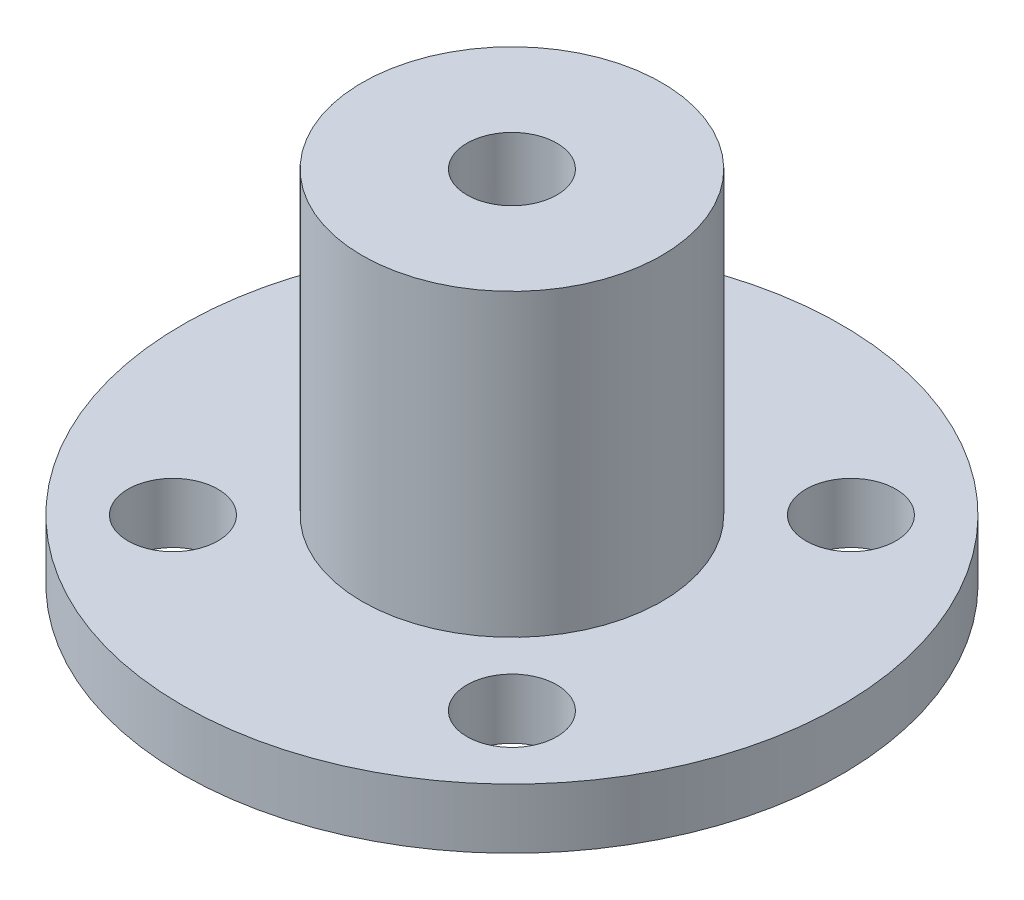
SolidWorks part; units mm, degrees
ref_plane "前视基准面" through (0, 0, 0) normal (0, 0, 1) x (1, 0, 0)
ref_plane "上视基准面" through (0, 0, 0) normal (0, 1, 0) x (1, 0, 0)
ref_plane "右视基准面" through (0, 0, 0) normal (1, 0, 0) x (0, 0, -1)
other "Configuration Table"
sketch "草图1" plane through (0, 0, 0) normal (0, 1, 0) x (1, 0, 0)
  line L1 (-5.6569, -5.6569) -> (5.6569, -5.6569) construction
  line L2 (-5.6569, -5.6569) -> (-5.6569, 5.6569) construction
  line L3 (-5.6569, 5.6569) -> (5.6569, 5.6569) construction
  line L4 (5.6569, -5.6569) -> (5.6569, 5.6569) construction
  line L5 (-5.6569, -5.6569) -> (5.6569, 5.6569) construction
  line L6 (-5.6569, 5.6569) -> (5.6569, -5.6569) construction
  circle A0 centre (0, 0) radius 11
  circle A1 centre (0, 0) radius 1.5
  circle A2 centre (0, 0) radius 8 construction
  circle A3 centre (5.6569, 5.6569) radius 1.5
  circle A4 centre (-5.6569, 5.6569) radius 1.5
  circle A5 centre (-5.6569, -5.6569) radius 1.5
  circle A6 centre (5.6569, -5.6569) radius 1.5
  dimension "D1" = 22
  dimension "D2" = 3
  dimension "D3" = 16
  dimension "D4" = 3
extrude "凸台-拉伸1" add sketch "草图1" along normal blind 2
sketch "草图2" plane through (0, 2, 0) normal (0, 1, 0) x (1, 0, 0)
  circle A0 centre (0, 0) radius 5
  circle A1 centre (0, 0) radius 1.5 construction
  circle A2 centre (0, 0) radius 1.5
  dimension "D1" = 10
extrude "凸台-拉伸2" add sketch "草图2" along normal blind 10
sketch "草图3" plane through (0, 0, 0) normal (0, 0, 1) x (1, 0, 0)
  line L0 (0, 12) -> (0, 0) construction
  line L1 (1.5, 12) -> (-1.5, 12) construction
  line L2 (-11, 0) -> (11, 0) construction
  circle A0 centre (0, 8) radius 1.5
  dimension "D1" = 8
  dimension "D2" = 3
extrude "切除-拉伸1" cut sketch "草图3" against normal blind 8
